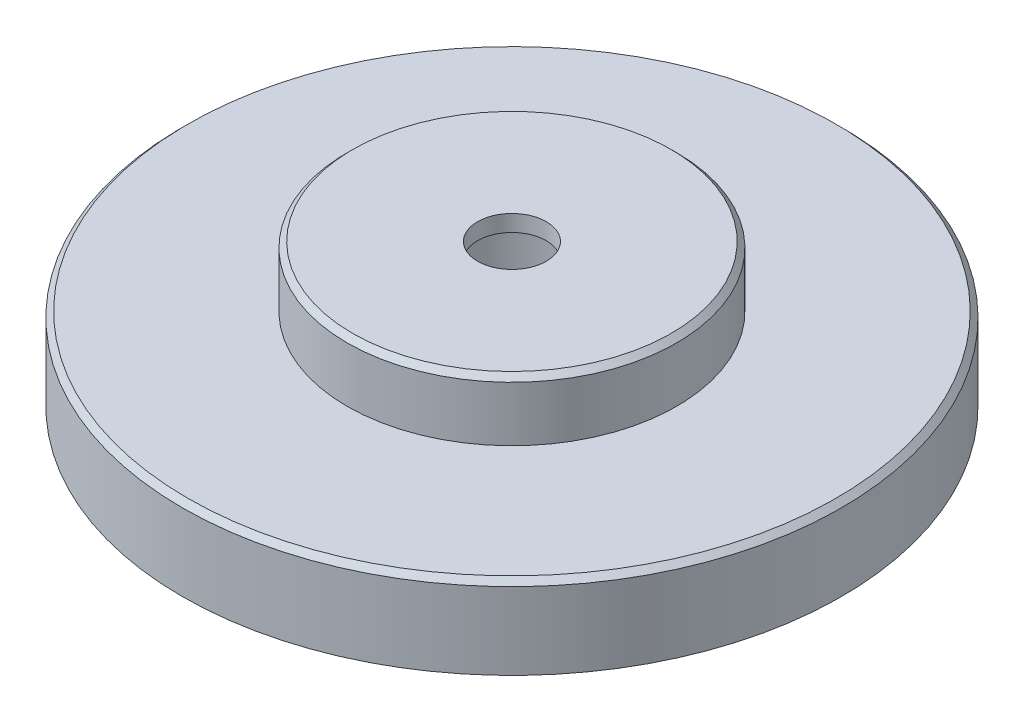
SolidWorks part; units mm, degrees
ref_plane "Front Plane" through (0, 0, 0) normal (0, 0, 1) x (1, 0, 0)
ref_plane "Top Plane" through (0, 0, 0) normal (0, 1, 0) x (1, 0, 0)
ref_plane "Right Plane" through (0, 0, 0) normal (1, 0, 0) x (0, 0, -1)
sketch "Sketch1" plane through (0, 0, 0) normal (0, 1, 0) x (1, 0, 0)
  line L1 (-4.9075, -8.5) -> (4.9075, -8.5)
  line L2 (4.9075, -8.5) -> (9.815, 0)
  line L3 (9.815, 0) -> (4.9075, 8.5)
  line L4 (4.9075, 8.5) -> (-4.9075, 8.5)
  line L5 (-4.9075, 8.5) -> (-9.815, 0)
  line L6 (-9.815, 0) -> (-4.9075, -8.5)
  circle A0 centre (0, 0) radius 8.5 construction
  circle A1 centre (0, 0) radius 12
  dimension "D2" = 24
  dimension "D1" = 17
extrude "Boss-Extrude1" add sketch "Sketch1" along normal blind 2
sketch "Sketch2" plane through (0, 2, 0) normal (0, 1, 0) x (1, 0, 0)
  circle A0 centre (0, 0) radius 12 construction
  circle A1 centre (0, 0) radius 12
extrude "Boss-Extrude2" add sketch "Sketch2" along normal blind 1
sketch "Sketch3" plane through (0, 3, 0) normal (0, 1, 0) x (1, 0, 0)
  circle A0 centre (0, 0) radius 6
  point P3 (0, 0)
  dimension "D1" = 12
extrude "Boss-Extrude3" add sketch "Sketch3" along normal blind 2.2
sketch "Sketch4" plane through (0, 2, 0) normal (0, -1, 0) x (1, 0, 0)
  circle A0 centre (0, 0) radius 3
  dimension "D1" = 6
extrude "Cut-Extrude1" cut sketch "Sketch4" against normal blind 2.6
sketch "Sketch5" plane through (0, 4.6, 0) normal (0, -1, 0) x (1, 0, 0)
  circle A0 centre (0, 0) radius 1.25
  dimension "D1" = 2.5
extrude "Cut-Extrude2" cut sketch "Sketch5" against normal up to next
chamfer "Chamfer1" distance 0.2 angle 45 2 edges at (0, 5.2, 6) (0, 3, 12)
